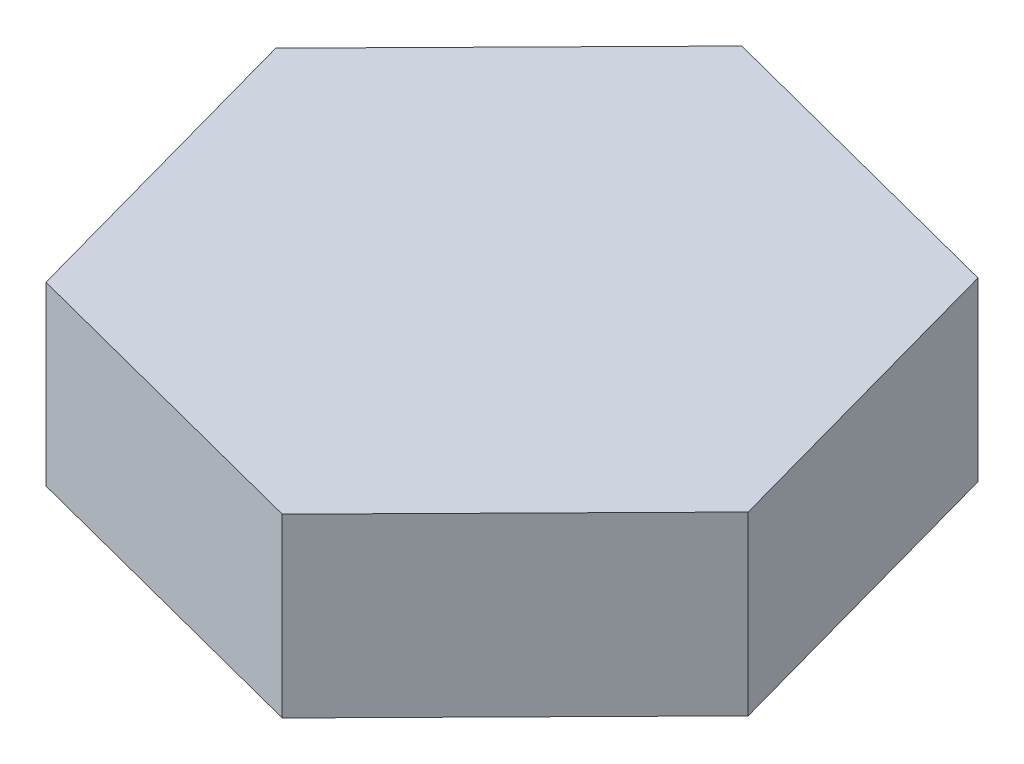
SolidWorks part; units mm, degrees
ref_plane "Front Plane" through (0, 0, 0) normal (0, 0, 1) x (1, 0, 0)
ref_plane "Top Plane" through (0, 0, 0) normal (0, 1, 0) x (1, 0, 0)
ref_plane "Right Plane" through (0, 0, 0) normal (1, 0, 0) x (0, 0, -1)
sketch "Sketch1" plane through (0, 0, 0) normal (0, 1, 0) x (1, 0, 0)
  line L1 (27.5624, 0.9762) -> (31.4904, 4.9679)
  line L2 (31.4904, 4.9679) -> (29.9974, 10.3656)
  line L3 (29.9974, 10.3656) -> (24.5764, 11.7714)
  line L4 (24.5764, 11.7714) -> (20.6484, 7.7797)
  line L5 (20.6484, 7.7797) -> (22.1414, 2.382)
  line L6 (22.1414, 2.382) -> (27.5624, 0.9762)
  circle A0 centre (26.0694, 6.3738) radius 4.85 construction
  dimension "D1" = 9.7
extrude "Boss-Extrude1" add sketch "Sketch1" along normal blind 3
